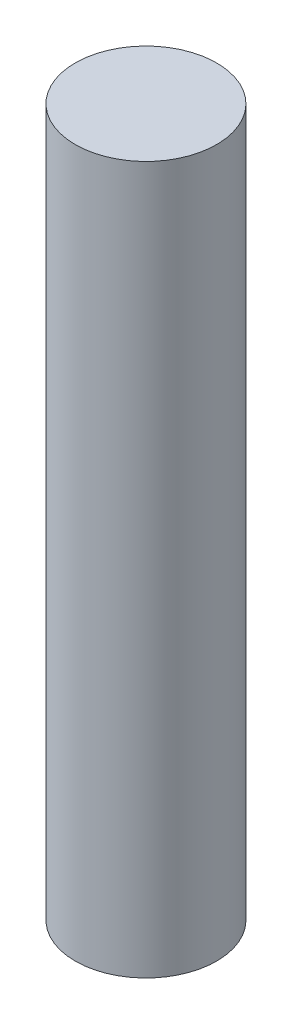
SolidWorks part; units mm, degrees
ref_plane "Alzado" through (0, 0, 0) normal (0, 0, 1) x (1, 0, 0)
ref_plane "Planta" through (0, 0, 0) normal (0, 1, 0) x (1, 0, 0)
ref_plane "Vista lateral" through (0, 0, 0) normal (1, 0, 0) x (0, 0, -1)
sketch "Sketch1" plane through (0, 0, 0) normal (0, 1, 0) x (1, 0, 0)
  circle A0 centre (0, 0) radius 1.5
  dimension "D1" = 3
extrude "Boss-Extrude1" add sketch "Sketch1" along normal blind 15
